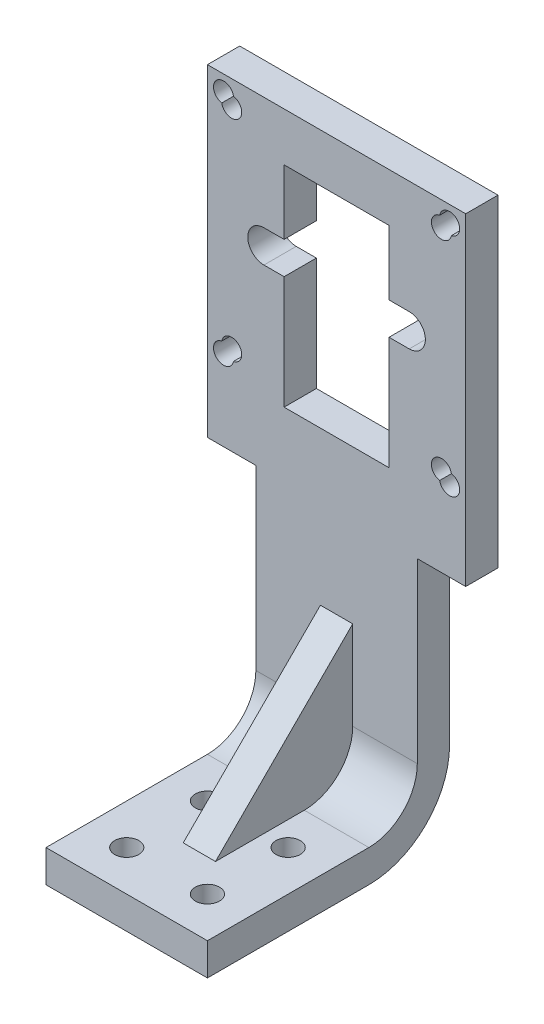
SolidWorks part; units mm, degrees
ref_plane "前视基准面" through (0, 0, 0) normal (0, 0, 1) x (1, 0, 0)
ref_plane "上视基准面" through (0, 0, 0) normal (0, 1, 0) x (1, 0, 0)
ref_plane "右视基准面" through (0, 0, 0) normal (1, 0, 0) x (0, 0, -1)
sketch "草图1" plane through (0, 0, 0) normal (0, 0, 1) x (1, 0, 0)
  line L0 (0, 20) -> (0, 0)
  line L1 (0, 0) -> (20, 0)
  line L2 (20, 0) -> (20, 20)
  line L3 (20, 20) -> (26, 20)
  line L4 (26, 20) -> (26, 60)
  line L5 (26, 60) -> (-6, 60)
  line L6 (-6, 60) -> (-6, 20)
  line L7 (-6, 20) -> (0, 20)
  line L8 (3.5, 54) -> (3.5, 46)
  line L9 (16.5, 54) -> (3.5, 54)
  line L10 (16.5, 46) -> (16.5, 54)
  line L11 (19, 46) -> (16.5, 46)
  line L12 (16.5, 42) -> (19, 42)
  line L13 (16.5, 28) -> (16.5, 42)
  line L14 (3.5, 28) -> (16.5, 28)
  line L15 (3.5, 28) -> (3.5, 42)
  line L16 (1, 42) -> (3.5, 42)
  line L17 (3.5, 46) -> (1, 46)
  arc A0 (24.2289, 56.7711) -> (22.7711, 58.2289) centre (24, 58) ccw
  arc A1 (22.7711, 58.2289) -> (24.2289, 56.7711) centre (23, 57) ccw
  arc A2 (24.2289, 31.2289) -> (22.7711, 29.7711) centre (23, 31) ccw
  arc A3 (22.7711, 29.7711) -> (24.2289, 31.2289) centre (24, 30) ccw
  arc A4 (19, 42) -> (19, 46) centre (19, 44) ccw
  arc A5 (-4.2289, 31.2289) -> (-2.7711, 29.7711) centre (-4, 30) ccw
  arc A6 (-2.7711, 29.7711) -> (-4.2289, 31.2289) centre (-3, 31) ccw
  arc A7 (-2.7711, 58.2289) -> (-4.2289, 56.7711) centre (-4, 58) ccw
  arc A8 (-4.2289, 56.7711) -> (-2.7711, 58.2289) centre (-3, 57) ccw
  arc A9 (1, 46) -> (1, 42) centre (1, 44) ccw
  dimension "D1" = 40
  dimension "D2" = 32
  dimension "D3" = 20
  dimension "D4" = 20
  dimension "D5" = 2
  dimension "D6" = 6
  dimension "D7" = 28
extrude "凸台-拉伸1" add sketch "草图1" along normal blind 4
sketch "草图4" plane through (0, 0, 0) normal (-1, 0, 0) x (0, 0, 1)
  line L0 (0, 0) -> (0, -2)
  line L1 (10, -12) -> (30, -12)
  line L2 (4, 0) -> (4, -2)
  line L3 (10, -8) -> (30, -8)
  line L4 (0, 0) -> (4, 0)
  line L5 (30, -8) -> (30, -12)
  arc A0 (0, -2) -> (10, -12) centre (10, -2) ccw
  arc A1 (4, -2) -> (10, -8) centre (10, -2) ccw
  dimension "D1" = 10
  dimension "D2" = 2
  dimension "D3" = 20
  dimension "D4" = 4
extrude "凸台-拉伸3" add sketch "草图4" against normal up to surface (20 mm away) up to face at (20, 10, 2)
ref_plane "基准面1" through (10, 0, 0) normal (-1, 0, 0) x (0, 0, 1)
sketch "草图5" plane through (10, 0, 0) normal (-1, 0, 0) x (0, 0, 1)
  line L0 (20.6421, -7.6421) -> (4, 9)
  line L2 (4, 20) -> (4, -2) construction
  line L3 (30, -8) -> (10, -8) construction
  dimension "D1" = 45
rib "筋1" sketch "草图5" sketch "草图5" thickness 4 extrusion direction parallel to sketch draft on no parameters "D1"=4
sketch "草图6" plane through (0, -12, 0) normal (0, -1, 0) x (1, 0, 0)
  line L1 (20, 30) -> (0, 30) construction
  line L2 (10, 16.5) -> (10, -16.5) construction
  circle A0 centre (5, 25) radius 1.5
  circle A3 centre (5, 15) radius 1.5
  circle A4 centre (15, 15) radius 1.5
  circle A6 centre (15, 25) radius 1.5
  circle A7 centre (5, 20) radius 1.5 [skipped]
  dimension "D1" = 3
  dimension "D2" = 5
  dimension "D3" = 3
  dimension "D4" = 10
extrude "切除-拉伸3" cut sketch "草图6" against normal blind 10
